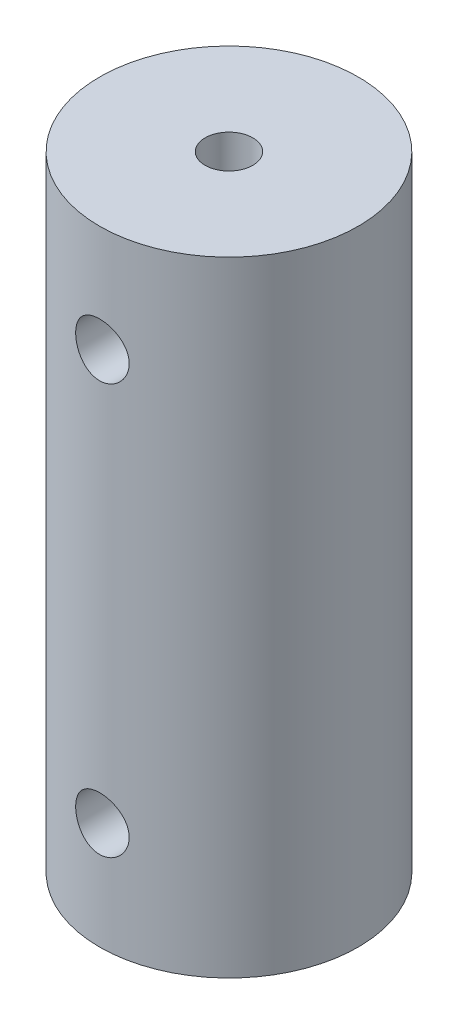
SolidWorks part; units mm, degrees
material "ABS"
ref_plane "Alzado" through (0, 0, 0) normal (0, 0, 1) x (1, 0, 0)
ref_plane "Planta" through (0, 0, 0) normal (0, 1, 0) x (1, 0, 0)
ref_plane "Vista lateral" through (0, 0, 0) normal (1, 0, 0) x (0, 0, -1)
sketch "Croquis2" plane through (0, 0, 0) normal (0, 1, 0) x (1, 0, 0)
  circle A0 centre (0, 0) radius 14.5
  dimension "D1" = 29
extrude "Saliente-Extruir1" add sketch "Croquis2" along normal mid plane 70
sketch "Croquis3" plane through (0, 35, 0) normal (0, 1, 0) x (1, 0, 0)
  circle A0 centre (0, 0) radius 2.675
  dimension "D1" = 5.35
extrude "Cortar-Extruir1" cut sketch "Croquis3" against normal blind 14
ref_plane "Plano1" through (0, 0, 14.5) normal (0, 0, 1) x (1, 0, 0)
sketch "Croquis7" plane through (0, 0, 14.5) normal (0, 0, 1) x (1, 0, 0)
  line L0 (2.675, 35) -> (-2.675, 35) construction
  circle A0 centre (0, 23) radius 3
  dimension "D1" = 6
  dimension "D2" = 12
extrude "Cortar-Extruir6" cut sketch "Croquis7" against normal blind 4.7
sketch "Croquis5" plane through (0, 0, 0) normal (0, 0, 1) x (1, 0, 0)
  line L0 (0, 23) -> (0, 25.5981) construction
  line L1 (-1.5, 20.4019) -> (1.5, 20.4019)
  line L2 (1.5, 20.4019) -> (3, 23)
  line L3 (3, 23) -> (1.5, 25.5981)
  line L4 (1.5, 25.5981) -> (-1.5, 25.5981)
  line L5 (-1.5, 25.5981) -> (-3, 23)
  line L6 (-3, 23) -> (-1.5, 20.4019)
  line L7 (14.5, 35) -> (-14.5, 35) construction
  circle A0 centre (0, 23) radius 2.5981 construction
  point P11 (0, 0)
  dimension "D1" = 3
  dimension "D2" = 12
extrude "Cortar-Extruir8" cut sketch "Croquis5" against normal blind 3 from surface at 9.8 starting at face at (3, 23, 9.8)
sketch "Croquis4" plane through (0, 0, 0) normal (0, 0, 1) x (1, 0, 0)
  line L1 (14.5, 35) -> (-14.5, 35) construction
  circle A0 centre (0, 23) radius 1.75
  dimension "D1" = 3.5
  dimension "D2" = 12
extrude "Cortar-Extruir2" cut sketch "Croquis4" along normal up to next
mirror "Simetría2" about plane through (0, 0, 0) normal (0, 1, 0) of "Cortar-Extruir2", "Cortar-Extruir8", "Cortar-Extruir6", "Cortar-Extruir1"
